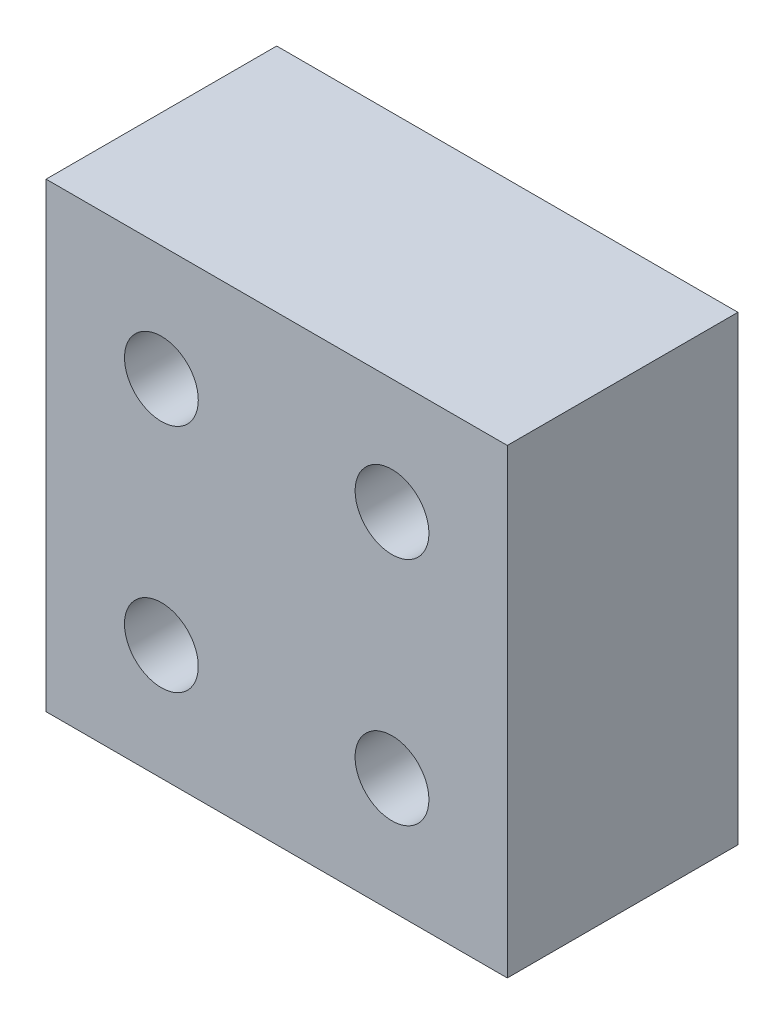
SolidWorks part; units mm, degrees
ref_plane "前视基准面" through (0, 0, 0) normal (0, 0, 1) x (1, 0, 0)
ref_plane "上视基准面" through (0, 0, 0) normal (0, 1, 0) x (1, 0, 0)
ref_plane "右视基准面" through (0, 0, 0) normal (1, 0, 0) x (0, 0, -1)
other "Configuration Table"
sketch "草图1" plane through (0, 0, 0) normal (0, 0, 1) x (1, 0, 0)
  line L1 (0, 0) -> (20, 0)
  line L2 (0, 0) -> (0, -20)
  line L3 (0, -20) -> (20, -20)
  line L4 (20, 0) -> (20, -20)
  dimension "D1" = 20
  dimension "D2" = 20
extrude "凸台-拉伸1" add sketch "草图1" along normal blind 10
sketch "草图2" plane through (0, 0, 10) normal (0, 0, 1) x (1, 0, 0)
  line L0 (0, -10) -> (20, -10) construction
  line L1 (0, 0) -> (0, -20) construction
  line L2 (20, -20) -> (20, 0) construction
  line L3 (10, 0) -> (10, -20) construction
  line L5 (20, 0) -> (0, 0) construction
  line L6 (0, -20) -> (20, -20) construction
  circle A0 centre (5, -5) radius 1.6
  circle A1 centre (15, -5) radius 1.6
  circle A2 centre (15, -15) radius 1.6
  circle A3 centre (5, -15) radius 1.6
  dimension "D1" = 3.2
  dimension "D2" = 5
  dimension "D3" = 5
extrude "切除-拉伸1" cut sketch "草图2" against normal through all
